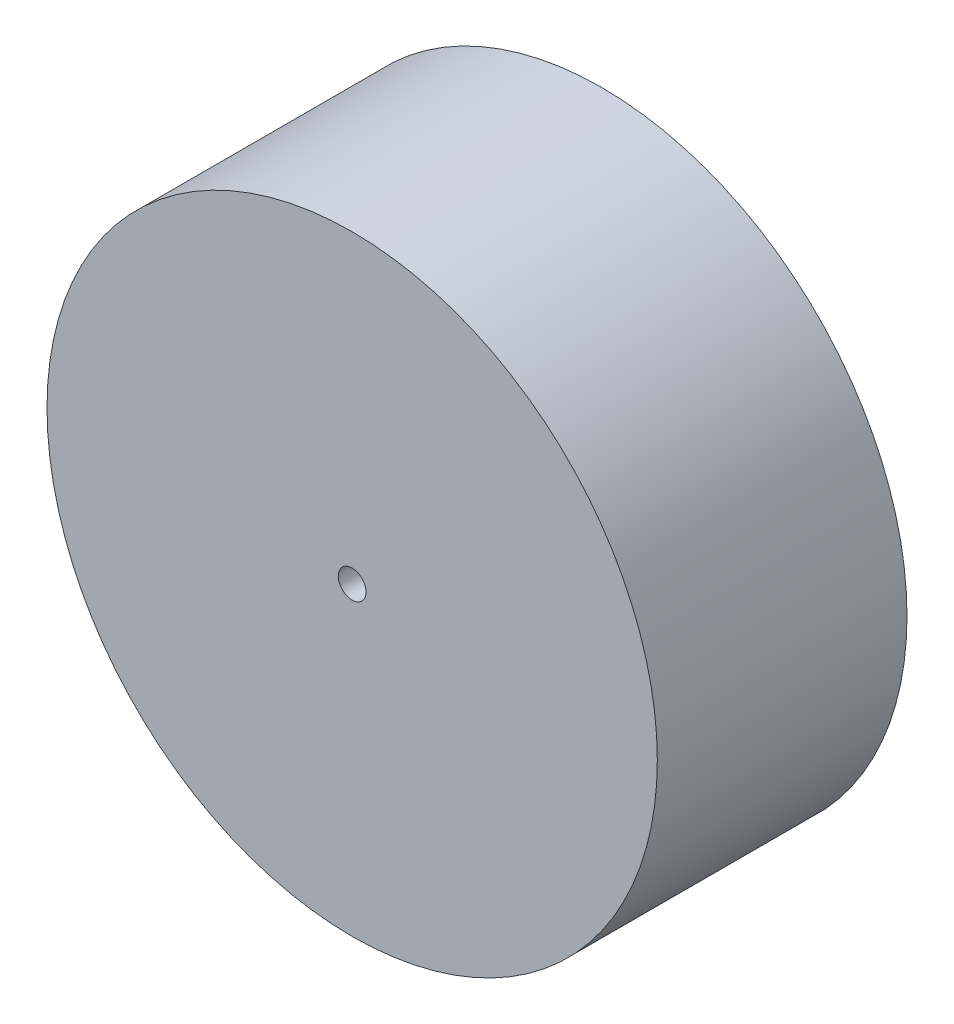
SolidWorks part; units mm, degrees
ref_plane "前视基准面" through (0, 0, 0) normal (0, 0, 1) x (1, 0, 0)
ref_plane "上视基准面" through (0, 0, 0) normal (0, 1, 0) x (1, 0, 0)
ref_plane "右视基准面" through (0, 0, 0) normal (1, 0, 0) x (0, 0, -1)
sketch "草图1" plane through (0, 0, 0) normal (0, 0, 1) x (1, 0, 0)
  circle A0 centre (0, 0) radius 33
extrude "凸台-拉伸1" add sketch "草图1" along normal blind 27
sketch "草图2" plane through (0, 0, 27) normal (0, 0, 1) x (1, 0, 0)
  circle A0 centre (0, 0) radius 1.5
  dimension "D1" = 3
extrude "切除-拉伸1" cut sketch "草图2" against normal through all
